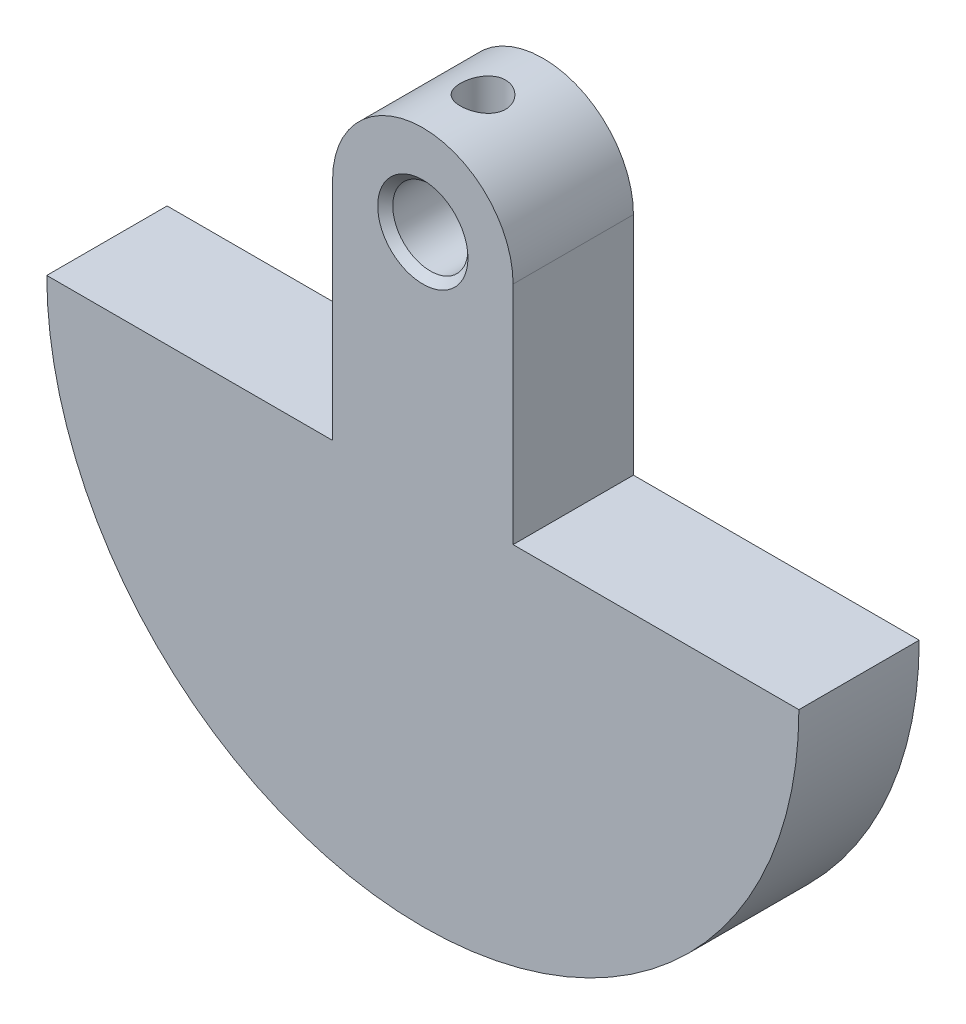
SolidWorks part; units mm, degrees
ref_plane "Front Plane" through (0, 0, 0) normal (0, 0, 1) x (1, 0, 0)
ref_plane "Top Plane" through (0, 0, 0) normal (0, 1, 0) x (1, 0, 0)
ref_plane "Right Plane" through (0, 0, 0) normal (1, 0, 0) x (0, 0, -1)
sketch "Sketch1" plane through (0, 0, 0) normal (0, 0, 1) x (1, 0, 0)
  line L0 (-6, 15) -> (-6, 0)
  line L1 (-6, 0) -> (-25, 0)
  line L2 (6, 15) -> (6, 0)
  line L3 (6, 0) -> (25, 0)
  arc A0 (-25, 0) -> (25, 0) centre (0, 0) ccw
  arc A1 (6, 15) -> (-6, 15) centre (0, 15) ccw
  circle A2 centre (0, 15) radius 2.5
  dimension "D1" = 50
  dimension "D2" = 12
  dimension "D4" = 5
  dimension "D3" = 15
extrude "Boss-Extrude1" add sketch "Sketch1" along normal blind 8
chamfer "Chamfer1" distance 0.5 angle 45 1 edges at (2.5, 15, 8)
ref_plane "Plane1" through (0, 21, 0) normal (0, 1, 0) x (1, 0, 0)
sketch "Sketch2" plane through (0, 21, 0) normal (0, 1, 0) x (1, 0, 0)
  line L0 (6, 0) -> (-6, 0) construction
  circle A0 centre (0, -4) radius 1.5
  dimension "D1" = 3
  dimension "D2" = 4
extrude "Cut-Extrude1" cut sketch "Sketch2" against normal blind 5
